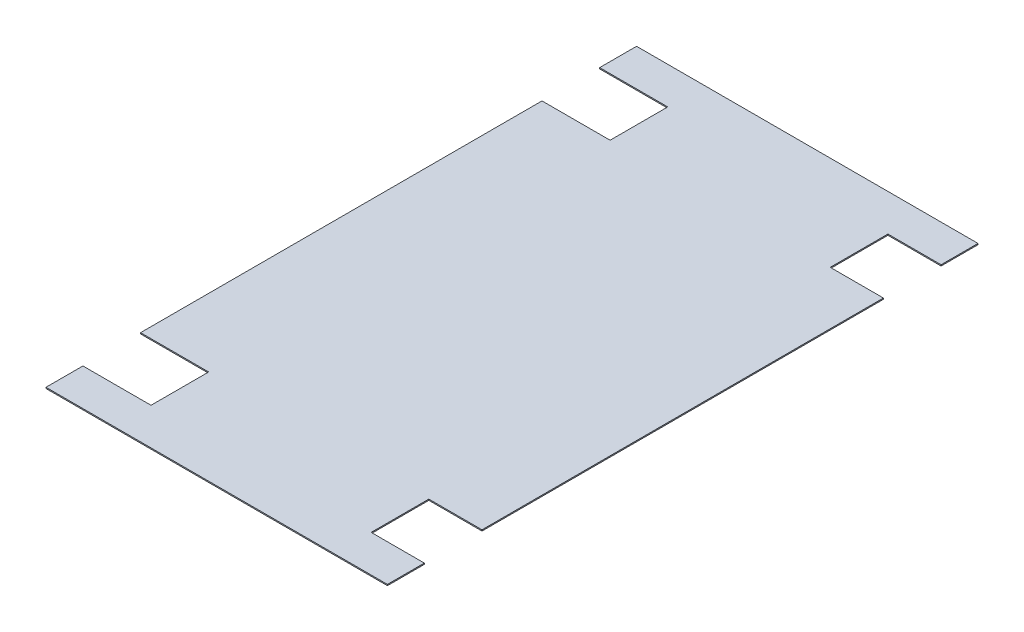
SolidWorks part; units mm, degrees
ref_plane "Front Plane" through (0, 0, 0) normal (0, 0, 1) x (1, 0, 0)
ref_plane "Top Plane" through (0, 0, 0) normal (0, 1, 0) x (1, 0, 0)
ref_plane "Right Plane" through (0, 0, 0) normal (1, 0, 0) x (0, 0, -1)
sketch "Sketch1" plane through (0, 0, 0) normal (0, 1, 0) x (1, 0, 0)
  line L1 (234.95, -406.4) -> (-234.95, -406.4)
  line L2 (234.95, -406.4) -> (234.95, 406.4)
  line L3 (234.95, 406.4) -> (-234.95, 406.4)
  line L4 (-234.95, -406.4) -> (-234.95, 406.4)
  line L5 (234.95, -406.4) -> (-234.95, 406.4) construction
  line L6 (234.95, 406.4) -> (-234.95, -406.4) construction
  point P0 (0, 0)
  dimension "D1" = 812.8
  dimension "D2" = 469.9
extrude "Boss-Extrude1" add sketch "Sketch1" along normal blind 1.5875
sketch "Sketch2" plane through (0, 1.5875, 0) normal (0, 1, 0) x (1, 0, 0)
  line L0 (-234.95, 355.6) -> (-234.95, 406.4)
  line L1 (-234.95, 406.4) -> (-234.95, -406.4) construction
  line L2 (-234.95, 406.4) -> (234.95, 406.4)
  line L3 (234.95, 406.4) -> (234.95, 355.6)
  line L4 (234.95, -406.4) -> (234.95, 406.4) construction
  line L5 (234.95, 355.6) -> (161.7697, 355.6)
  line L6 (161.7697, 355.6) -> (161.7697, 276.225)
  line L7 (161.7697, 276.225) -> (234.95, 276.225)
  line L8 (234.95, 276.225) -> (234.95, -276.225)
  line L9 (234.95, -276.225) -> (161.7697, -276.225)
  line L10 (161.7697, -276.225) -> (161.7697, -355.6)
  line L11 (161.7697, -355.6) -> (234.95, -355.6)
  line L12 (234.95, -355.6) -> (234.95, -406.4)
  line L13 (234.95, -406.4) -> (-234.95, -406.4)
  line L14 (-234.95, -406.4) -> (-234.95, -355.6)
  line L15 (-234.95, -355.6) -> (-141.2207, -355.6)
  line L16 (-141.2207, -355.6) -> (-141.2207, -276.225)
  line L17 (-141.2207, -276.225) -> (-234.95, -276.225)
  line L18 (-234.95, -276.225) -> (-234.95, 276.225)
  line L19 (-234.95, 276.225) -> (-141.2207, 276.225)
  line L20 (-141.2207, 276.225) -> (-141.2207, 355.6)
  line L21 (-141.2207, 355.6) -> (-234.95, 355.6)
  dimension "D1" = 79.375
  dimension "D2" = 50.8
extrude "Cut-Extrude1" cut sketch "Sketch2" against normal blind 1.5875 flip side to cut
